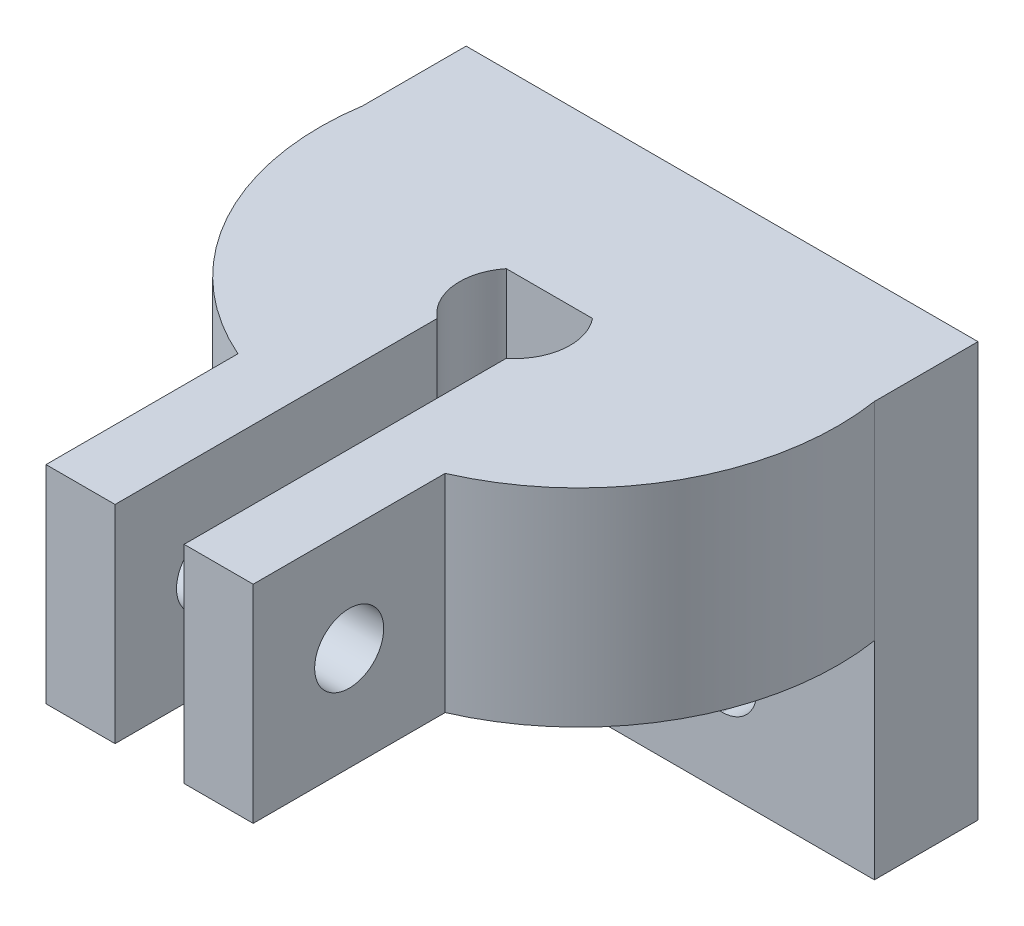
SolidWorks part; units mm, degrees
material "CA"
ref_plane "Front Plane" through (0, 0, 0) normal (0, 0, 1) x (1, 0, 0)
ref_plane "Top Plane" through (0, 0, 0) normal (0, 1, 0) x (1, 0, 0)
ref_plane "Right Plane" through (0, 0, 0) normal (1, 0, 0) x (0, 0, -1)
sketch "Sketch3" plane through (0, 0, 0) normal (0, 1, 0) x (1, 0, 0)
  line L0 (-6.25, 4.1458) -> (6.25, 4.1458)
  arc A0 (-6.25, 4.1458) -> (6.25, 4.1458) centre (0, 0) ccw
  dimension "D1" = 15
  dimension "D2" = 12.5
extrude "Boss-Extrude1" add sketch "Sketch3" along normal blind 6
sketch "Sketch7" plane through (0, 0, 0) normal (0, -1, 0) x (1, 0, 0)
  line L0 (6.25, -4.1458) -> (-6.25, -4.1458) construction
  line L1 (6.25, -4.1458) -> (-6.25, -4.1458)
  line L2 (-7.412, -1.1458) -> (7.412, -1.1458)
  arc A0 (6.25, -4.1458) -> (-6.25, -4.1458) centre (0, 0) ccw construction
  arc A1 (6.25, -4.1458) -> (7.412, -1.1458) centre (0, 0) ccw
  arc A2 (-7.412, -1.1458) -> (-6.25, -4.1458) centre (0, 0) ccw
  dimension "D1" = 3
extrude "Boss-Extrude4" add sketch "Sketch7" along normal blind 6
sketch "Sketch4" plane through (0, 6, 0) normal (0, 1, 0) x (1, 0, 0)
  line L0 (-1.249, -0.8542) -> (1.249, -0.8542)
  line L1 (6.25, 4.1458) -> (-6.25, 4.1458) construction
  arc A0 (-1.249, -0.8542) -> (1.249, -0.8542) centre (0, -1.8542) ccw
  dimension "D1" = 3.2
  dimension "D2" = 1
  dimension "D3" = 5
extrude "Cut-Extrude1" cut sketch "Sketch4" against normal blind 8
sketch "Sketch9" plane through (0, -6, 0) normal (0, -1, 0) x (1, 0, 0)
  line L0 (-7.412, -1.1458) -> (-7.412, -4.1458)
  line L1 (-7.412, -4.1458) -> (7.412, -4.1458)
  line L2 (7.412, -4.1458) -> (7.412, -1.1458)
  line L3 (7.412, -1.1458) -> (-7.412, -1.1458)
extrude "Boss-Extrude5" add sketch "Sketch9" against normal up to surface (12 mm away)
sketch "Sketch8" plane through (0, 0, -1.1458) normal (0, 0, 1) x (1, 0, 0)
  line L0 (-3, -3) -> (3, -3) construction
  line L1 (-3, -2) -> (3, -2)
  line L2 (3, -4) -> (-3, -4)
  line L3 (-7.412, -6) -> (-7.412, 0) construction
  line L4 (7.412, -6) -> (-7.412, -6) construction
  arc A0 (-3, -2) -> (-3, -4) centre (-3, -3) ccw
  arc A1 (3, -4) -> (3, -2) centre (3, -3) ccw
  point P2 (-7.412, -3)
  point P3 (0, -3)
  point P10 (0, -6)
  dimension "D1" = 2
  dimension "D2" = 6
extrude "Cut-Extrude3" cut sketch "Sketch8" against normal blind 10
sketch "Sketch11" plane through (0, 6, 0) normal (0, 1, 0) x (1, 0, 0)
  line L0 (-1, -7.433) -> (-1, -3.1032)
  line L2 (1, -3.1032) -> (1, -7.433)
  arc A0 (-7.412, 1.1458) -> (7.412, 1.1458) centre (0, 0) ccw construction
  arc A1 (-1.249, -0.8542) -> (1.249, -0.8542) centre (0, -1.8542) ccw construction
  arc A2 (-1, -3.1032) -> (1, -3.1032) centre (0, -1.8542) ccw
  arc A3 (-1, -7.433) -> (1, -7.433) centre (0, 0) ccw
  point P8 (0, -3.4542)
  dimension "D1" = 2
  dimension "D2" = 1
extrude "Cut-Extrude4" cut sketch "Sketch11" against normal through all
sketch "Sketch12" plane through (-1, 0, 0) normal (1, 0, 0) x (0, 0, -1)
  line L1 (-5.433, 0) -> (-12.433, 0)
  line L2 (-5.433, 0) -> (-5.433, 6)
  line L3 (-5.433, 6) -> (-12.433, 6)
  line L4 (-12.433, 0) -> (-12.433, 6)
  line L5 (-7.433, 0) -> (-7.433, 6) construction
  point P6 (-5.433, 3)
  point P16 (-7.433, 3)
  dimension "D1" = 7
  dimension "D2" = 6
  dimension "D3" = 2
extrude "Boss-Extrude6" add sketch "Sketch12" against normal blind 2
mirror "Mirror1" about plane through (0, 0, 0) normal (1, 0, 0) of "Boss-Extrude6"
sketch "Sketch13" plane through (-3, 0, 0) normal (-1, 0, 0) x (0, 0, 1)
  line L0 (12.433, 6) -> (12.433, 0) construction
  line L1 (6.8739, 6) -> (12.433, 6) construction
  circle A0 centre (9.6534, 3) radius 1
  point P5 (12.433, 3)
  point P9 (9.6534, 6)
  dimension "D1" = 2
extrude "Cut-Extrude5" cut sketch "Sketch13" against normal through all
